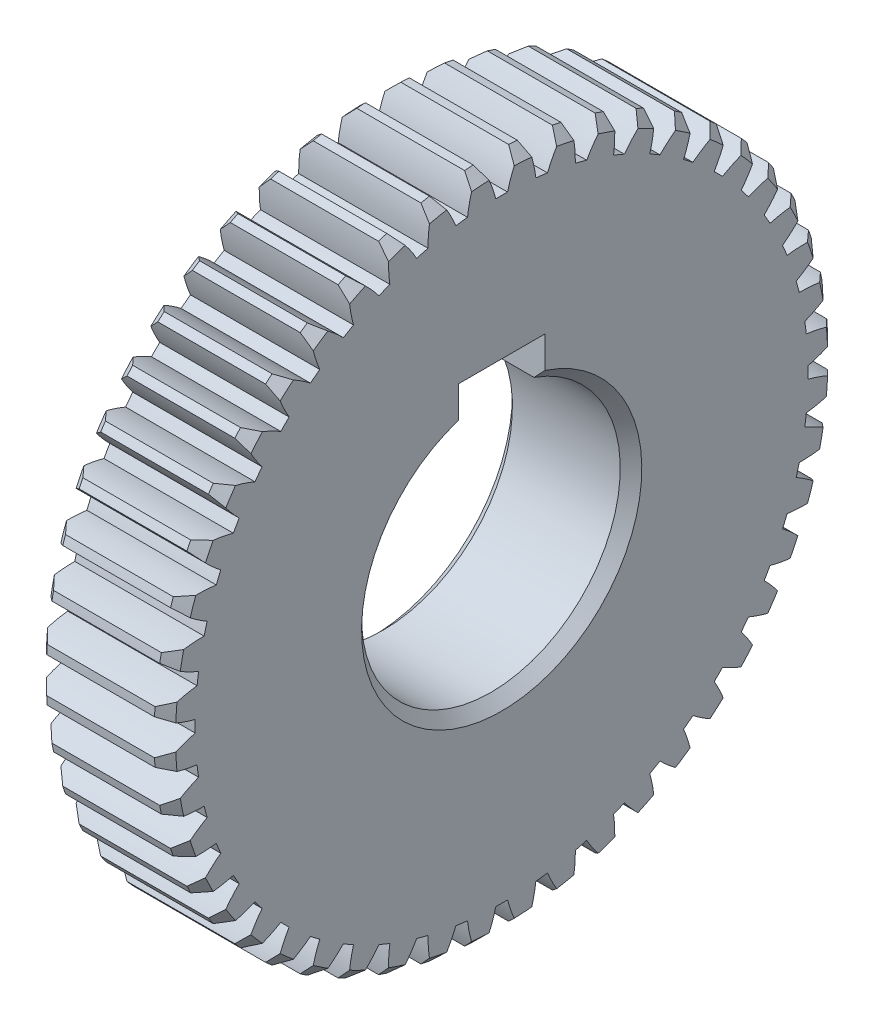
SolidWorks part; units mm, degrees
ref_plane "Plane1" through (0, 0, 0) normal (0, 0, 1) x (1, 0, 0)
ref_plane "Plane2" through (0, 0, 0) normal (0, 1, 0) x (1, 0, 0)
ref_plane "Plane3" through (0, 0, 0) normal (1, 0, 0) x (0, 0, -1)
sketch "HoldingSke" plane through (0, 0, 0) normal (0, 1, 0) x (1, 0, 0)
  line L0 (0, 0) -> (0.5353, -0.5945)
  line L1 (-15, 0) -> (100, 0) construction
  line L2 (0, 0) -> (-2.1039, 2.3779)
  line L3 (0, 0) -> (-11.863, 4.5341)
  line L4 (0, 0) -> (5.7786, 6.4178)
  line L5 (0, 0) -> (-46.8476, -17.4728)
  line L6 (0, 0) -> (-9.9476, -6.7116)
  line L7 (-2.1039, 2.3779) -> (8.6586, 51.2059)
  line L8 (-76.2, 54.61) -> (-72.9, 54.61)
  line L9 (-71.009, 38.7566) -> (-53.1078, 45.2721)
  line L10 (-76.2, 71.12) -> (104.1128, 71.12)
  line L11 (0, 0) -> (-12, 0)
  line L12 (-76.2, 101.6) -> (-76.155, 101.6)
  line L13 (24.9733, 27.94) -> (52.9518, 28.4284)
  line L14 (24.9733, 27.94) -> (24.9743, 27.94)
  line L15 (24.9733, 27.94) -> (100.4006, 29.5858)
  line L16 (-63.627, -1.25) -> (-12.827, -1.25)
  circle A0 centre (0, 0) radius 12
  circle A1 centre (0, 0) radius 28.4365
  circle A2 centre (0, 0) radius 37.5
  circle A3 centre (0, 0) radius 12
  dimension "MHD" = 56.873
  dimension "Hub_dia" = 75
  dimension "Bore" = 24
  dimension "MBD" = 24
  dimension "Num_teeth" = 48
  dimension "Pitch" = 0.8
  dimension "Overall_len" = 50
  dimension "Show_teeth" = 48
  dimension "Thickness" = 12
  dimension "OAL" = 50.0001
  dimension "T_dim" = 3.3
  dimension "Ap" = 20
  dimension "H" = 19.05
  dimension "Pitch_radius" = 180.3128
  dimension "Width" = 12
  dimension "Backlash" = 0.045
  dimension "Addendum_fac" = 1
  dimension "Dedendum_fac" = 1.25
  dimension "Clearance_fac" = 0.25
  dimension "Dedendum_add" = 0.001
  dimension "Module" = 1.25
sketch "BasProSke" plane through (0, 0, 0) normal (0, 1, 0) x (1, 0, 0)
  line L0 (-10, 0) -> (60, 0) construction
  line L1 (0, 0) -> (0, 31.25)
  line L2 (0, 0) -> (12, 0)
  line L3 (12, 0) -> (12, 31.25)
  line L4 (12, 31.25) -> (0, 31.25)
  dimension "Thickness" = 12
  dimension "Diameter" = 62.5
revolve "Base-Revolve" add sketch "BasProSke" angle 360 about L0
sketch "TooCutSke" plane through (0, 0, 0) normal (1, 0, 0) x (0, 0, -1)
  line L1 (0, 0) -> (0, 107) construction
  line L2 (0, 0) -> (-1.0603, 29.9813) construction
  line L3 (0, 0) -> (-3.9224, 59.8444) construction
  line L4 (-1.0603, 29.9813) -> (-1.9612, 29.9222) construction
  arc A0 (0.5453, 28.4313) -> (-0.5453, 28.4313) centre (0, 0) ccw
  arc A1 (1.6591, 31.2314) -> (-1.6591, 31.2314) centre (0, 0) ccw
  circle A2 centre (0, 0) radius 30 construction
  circle A3 centre (0, 0) radius 28.1908 construction
  arc A4 (-0.5453, 28.4313) -> (-1.6591, 31.2314) centre (-12.1643, 25.4313) ccw
  arc A5 (1.6591, 31.2314) -> (0.5453, 28.4313) centre (12.1643, 25.4313) ccw
  dimension "Root_dia" = 56.873
  dimension "Overcut_dia" = 62.5508
  dimension "Pitch_dia" = 60
  dimension "Base_dia" = 56.3816
  dimension "Flank_rad" = 12
  dimension "Half_ang" = 3.75
  dimension "Half_CT" = 0.9028
extrude "ToothCut" cut sketch "TooCutSke" along normal through all
fillet "Breaks" [suppressed] radius 0.025
fillet "RootFillets" [suppressed] radius 0.3135
pattern_circular "TeethCuts" count 48 every 7.5 about axis through (-10, 0, 0) along (1, 0, 0) of "ToothCut", "RootFillets", "Breaks"
sketch "HubNeaOneSke" plane through (0, 0, 0) normal (-1, 0, 0) x (0, 0, 1)
  circle A0 centre (0, 0) radius 28.4365
  dimension "Diameter" = 56.873
extrude "HubNearOne" [suppressed] add sketch "HubNeaOneSke" along normal blind 38.0001
sketch "HubNeaBotSke" plane through (0, 0, 0) normal (-1, 0, 0) x (0, 0, 1)
  circle A0 centre (0, 0) radius 28.4365
  dimension "Diameter" = 56.873
extrude "HubNearBoth" [suppressed] add sketch "HubNeaBotSke" along normal blind 19
ref_plane "FarPln" through (12, 0, 0) normal (1, 0, 0) x (0, 0, -1)
sketch "HubFarSke" plane through (12, 0, 0) normal (1, 0, 0) x (0, 0, -1)
  circle A0 centre (0, 0) radius 28.4365
  dimension "Diameter" = 56.873
extrude "HubFar" [suppressed] add sketch "HubFarSke" along normal blind 19
sketch "BorSke" plane through (0, 0, 0) normal (1, 0, 0) x (0, 0, -1)
  circle A0 centre (0, 0) radius 12
  dimension "Diameter" = 24
extrude "Bore" cut sketch "BorSke" along normal mid plane 100.0001
sketch "KeySke" plane through (0, 0, 0) normal (1, 0, 0) x (0, 0, -1)
  line L0 (-4, 0) -> (-4, 15.3)
  line L1 (-4, 15.3) -> (4, 15.3)
  line L2 (4, 15.3) -> (4, 0)
  line L3 (0, 0) -> (0, 34) construction
  line L4 (-4, 0) -> (4, 0)
  dimension "Offset" = 15.3
  dimension "Width" = 8
extrude "Keyway" cut sketch "KeySke" along normal mid plane 100.0001
pattern_circular "Keyway2" [suppressed] count 2 every 90 about axis through (-10, 0, 0) along (1, 0, 0)
chamfer "Chamfer1" distance 1 angle 45 2 edges at (12, -12, 0) (0, -12, 0)
chamfer "Chamfer2" distance 1 angle 45 96 edges at (0, 10.045, -29.5916) (12, 10.045, -29.5916) (0, -25.9834, 17.3616) (0, -28.0273, 13.8215) (0, -29.5916, 10.045) (0, -30.6495, 6.0966) (0, -31.1831, 2.0438) (0, -31.1831, -2.0438) (0, -30.6495, -6.0966) (0, -29.5916, -10.045) (0, -28.0273, -13.8215) (0, -25.9834, -17.3616) (0, -23.495, -20.6046) (0, -20.6046, -23.495) (0, -17.3616, -25.9834) (0, -13.8215, -28.0273) (0, -23.495, 20.6046) (0, -20.6046, 23.495) (0, -17.3616, 25.9834) (0, -13.8215, 28.0273) (0, -10.045, 29.5916) (0, -6.0966, 30.6495) (0, -2.0438, 31.1831) (0, 2.0438, 31.1831) (0, 6.0966, 30.6495) (0, 10.045, 29.5916) (0, 13.8215, 28.0273) (0, 17.3616, 25.9834) (0, 20.6046, 23.495) (0, 23.495, 20.6046) (0, 25.9834, 17.3616) (0, 28.0273, 13.8215) (0, 29.5916, 10.045) (0, 30.6495, 6.0966) (0, 31.1831, 2.0438) (0, 31.1831, -2.0438) (0, 29.5916, -10.045) (0, 30.6495, -6.0966) (0, 28.0273, -13.8215) (0, -10.045, -29.5916) (0, -6.0966, -30.6495) (0, -2.0438, -31.1831) (0, 2.0438, -31.1831) (0, 6.0966, -30.6495) (0, 25.9834, -17.3616) (0, 23.495, -20.6046) (0, 20.6046, -23.495) (0, 17.3616, -25.9834) (0, 13.8215, -28.0273) (12, -30.6495, 6.0966) (12, -29.5916, 10.045) (12, -28.0273, 13.8215) (12, -25.9834, 17.3616) (12, -23.495, 20.6046) (12, -20.6046, 23.495) (12, -17.3616, 25.9834) (12, -13.8215, 28.0273) (12, -10.045, 29.5916) (12, -6.0966, 30.6495) (12, -2.0438, 31.1831) (12, 2.0438, 31.1831) (12, 6.0966, 30.6495) (12, 10.045, 29.5916) (12, 13.8215, 28.0273) (12, 17.3616, 25.9834) (12, 20.6046, 23.495) (12, 23.495, 20.6046) (12, 25.9834, 17.3616) (12, 28.0273, 13.8215) (12, 29.5916, 10.045) (12, 30.6495, 6.0966) (12, 31.1831, 2.0438) (12, 31.1831, -2.0438) (12, 30.6495, -6.0966) (12, 29.5916, -10.045) (12, 28.0273, -13.8215) (12, 25.9834, -17.3616) (12, 23.495, -20.6046) (12, -31.1831, 2.0438) (12, -31.1831, -2.0438) (12, -30.6495, -6.0966) (12, -29.5916, -10.045) (12, -28.0273, -13.8215) (12, -25.9834, -17.3616) (12, -23.495, -20.6046) (12, -20.6046, -23.495) (12, -17.3616, -25.9834) (12, -13.8215, -28.0273) (12, -10.045, -29.5916) (12, -6.0966, -30.6495) (12, 20.6046, -23.495) (12, 17.3616, -25.9834) (12, 13.8215, -28.0273) (12, -2.0438, -31.1831) (12, 2.0438, -31.1831) (12, 6.0966, -30.6495)
equation "' \"Module@HoldingSke\" = 6.35"
equation "' \"Num_teeth@HoldingSke\" = 12"
equation "' \"Ap@HoldingSke\" =  20"
equation "' \"Ap@HoldingSke\" = 20"
equation "' \"Width@HoldingSke\" = 0.5 * 25.4"
equation "' \"Hub_dia@HoldingSke\"= 1 * 25.4"
equation "' \"Hub_dia@HoldingSke\" = 1 * 25.4"
equation "' \"Overall_len@HoldingSke\" = 1.0 * 25.4"
equation "' \"Bore@HoldingSke\" = 0.75 * 25.4"
equation "' \"T_dim@HoldingSke\" = 0.1 * 25.4"
equation "' \"Width@KeySke\" = 0.25 * 25.4"
equation "' \"Show_teeth@HoldingSke\" = 13"
equation "' \"Backlash@HoldingSke\" = 0.009 * 25.4"
equation "' \"Addendum_fac@HoldingSke\" = 1.0"
equation "' \"Dedendum_fac@HoldingSke\" = 1.25"
equation "' \"Dedendum_add@HoldingSke\" = 0.00005 * 25.4"
equation "' \"Clearance_fac@HoldingSke\" = 0.25"
equation "\"Pitch@HoldingSke\" = 1 / \"Module@HoldingSke\""
equation "\"Overcut_dia@TooCutSke\" = (\"Num_teeth@HoldingSke\" + 2 * \"Addendum_fac@HoldingSke\") / \"Pitch@HoldingSke\" + 0.002 * 25.4"
equation "\"Pitch_dia@TooCutSke\" = \"Num_teeth@HoldingSke\" / \"Pitch@HoldingSke\""
equation "\"Base_dia@TooCutSke\" = \"Num_teeth@HoldingSke\" / \"Pitch@HoldingSke\" * cos((\"Ap@HoldingSke\"  * 3.14159265 / 180))"
equation "\"Root_dia@TooCutSke\" = (\"Num_teeth@HoldingSke\" + 2) / \"Pitch@HoldingSke\" - 2 * (\"Addendum_fac@HoldingSke\" + \"Dedendum_fac@HoldingSke\") / \"Pitch@HoldingSke\" - \"Dedendum_add@HoldingSke\" * 2"
equation "\"Half_ang@TooCutSke\" = 180 / \"Num_teeth@HoldingSke\""
equation "\"Half_CT@TooCutSke\" = \"Num_teeth@HoldingSke\" / \"Pitch@HoldingSke\" * sin((3.14159265 / 2 / \"Num_teeth@HoldingSke\")) / 2 - 7 * \"Backlash@HoldingSke\" / 4"
equation "\"Flank_rad@TooCutSke\" = \"Num_teeth@HoldingSke\" / \"Pitch@HoldingSke\" / 5"
equation "\"Radius@RootFillets\" = \"Clearance_fac@HoldingSke\" / \"Pitch@HoldingSke\" + \"Dedendum_add@HoldingSke\""
equation "\"Break_rad@Breaks\" = 0.02 / \"Pitch@HoldingSke\""
equation "\"Thickness@HoldingSke\" = \"Width@HoldingSke\""
equation "\"OAL@HoldingSke\" = \"Thickness@HoldingSke\""
equation "\"MHD@HoldingSke\" = (\"Num_teeth@HoldingSke\" + 2) / \"Pitch@HoldingSke\" - 2 * (\"Addendum_fac@HoldingSke\" + \"Dedendum_fac@HoldingSke\")  / \"Pitch@HoldingSke\" - \"Dedendum_add@HoldingSke\" * 2"
equation "\"MBD@HoldingSke\" = (\"Num_teeth@HoldingSke\" + 2) / \"Pitch@HoldingSke\" - 2 * (\"Addendum_fac@HoldingSke\" + \"Dedendum_fac@HoldingSke\")  / \"Pitch@HoldingSke\" - \"Dedendum_add@HoldingSke\" * 2 - 0.002 * 25.4"
equation "\"MHD@HoldingSke\" = ((sgn( \"MHD@HoldingSke\" - \"Hub_dia@HoldingSke\" )-1)*( \"MHD@HoldingSke\" - \"Hub_dia@HoldingSke\" ))/-2+ \"Hub_dia@HoldingSke\""
equation "\"MBD@HoldingSke\" = ((sgn( \"MBD@HoldingSke\" - \"Bore@HoldingSke\" )-1)*( \"MBD@HoldingSke\" - \"Bore@HoldingSke\" ))/-2+ \"Bore@HoldingSke\""
equation "\"OAL@HoldingSke\" = ((sgn( \"OAL@HoldingSke\" - \"Overall_len@HoldingSke\" )+1)*( \"OAL@HoldingSke\" - \"Overall_len@HoldingSke\" ))/2 + \"Overall_len@HoldingSke\" + 0.000002 * 25.4"
equation "\"Num_teeth@TeethCuts\" = int( \"Show_teeth@HoldingSke\" ) + 1"
equation "\"Num_teeth@TeethCuts\" = ((sgn( \"Num_teeth@TeethCuts\" - \"Num_teeth@HoldingSke\" )-1)*( \"Num_teeth@TeethCuts\" - \"Num_teeth@HoldingSke\" ))/-2+ \"Num_teeth@HoldingSke\""
equation "\"Num_teeth@TeethCuts\" = ((sgn( \"Num_teeth@TeethCuts\" - 2.0)+1)*( \"Num_teeth@TeethCuts\" - 2.0))/2 +2.0"
equation "\"Angle@TeethCuts\" = 360.0 / \"Num_teeth@HoldingSke\""
equation "\"Diameter@BasProSke\" = (\"Num_teeth@HoldingSke\" + 2 * \"Addendum_fac@HoldingSke\") / \"Pitch@HoldingSke\""
equation "\"Thickness@BasProSke\"  = \"Thickness@HoldingSke\""
equation "' \"Fillet_rad@BasProSke\" =  \"Thickness@HoldingSke\" * 0.05"
equation "' \"Fillet_rad@BasProSke\" = \"Thickness@HoldingSke\" * 0.05"
equation "\"MHD@HoldingSke\" = ((sgn( \"MHD@HoldingSke\" - \"Root_dia@TooCutSke\" )-1)*( \"MHD@HoldingSke\" - \"Root_dia@TooCutSke\" ))/-2+ \"Root_dia@TooCutSke\""
equation "\"Diameter@HubNeaOneSke\" = \"MHD@HoldingSke\""
equation "\"Length@HubNearOne\" = \"OAL@HoldingSke\" - \"Thickness@BasProSke\""
equation "\"Diameter@HubNeaBotSke\" = \"MHD@HoldingSke\""
equation "\"Length@HubNearBoth\" = ( \"OAL@HoldingSke\" - \"Thickness@BasProSke\" ) / 2.0"
equation "\"Thickness@FarPln\" = \"Thickness@BasProSke\""
equation "\"Diameter@HubFarSke\" = \"MHD@HoldingSke\""
equation "\"Length@HubFar\" = ( \"OAL@HoldingSke\" - \"Thickness@BasProSke\" ) / 2.0"
equation "\"Diameter@BorSke\" = \"MBD@HoldingSke\""
equation "\"D1@Bore\" = \"OAL@HoldingSke\" * 2.0"
equation "\"D1@Keyway\" = \"OAL@HoldingSke\" * 2.0"
equation "\"Offset@KeySke\" = \"T_dim@HoldingSke\" + \"MBD@HoldingSke\" / 2.0"
